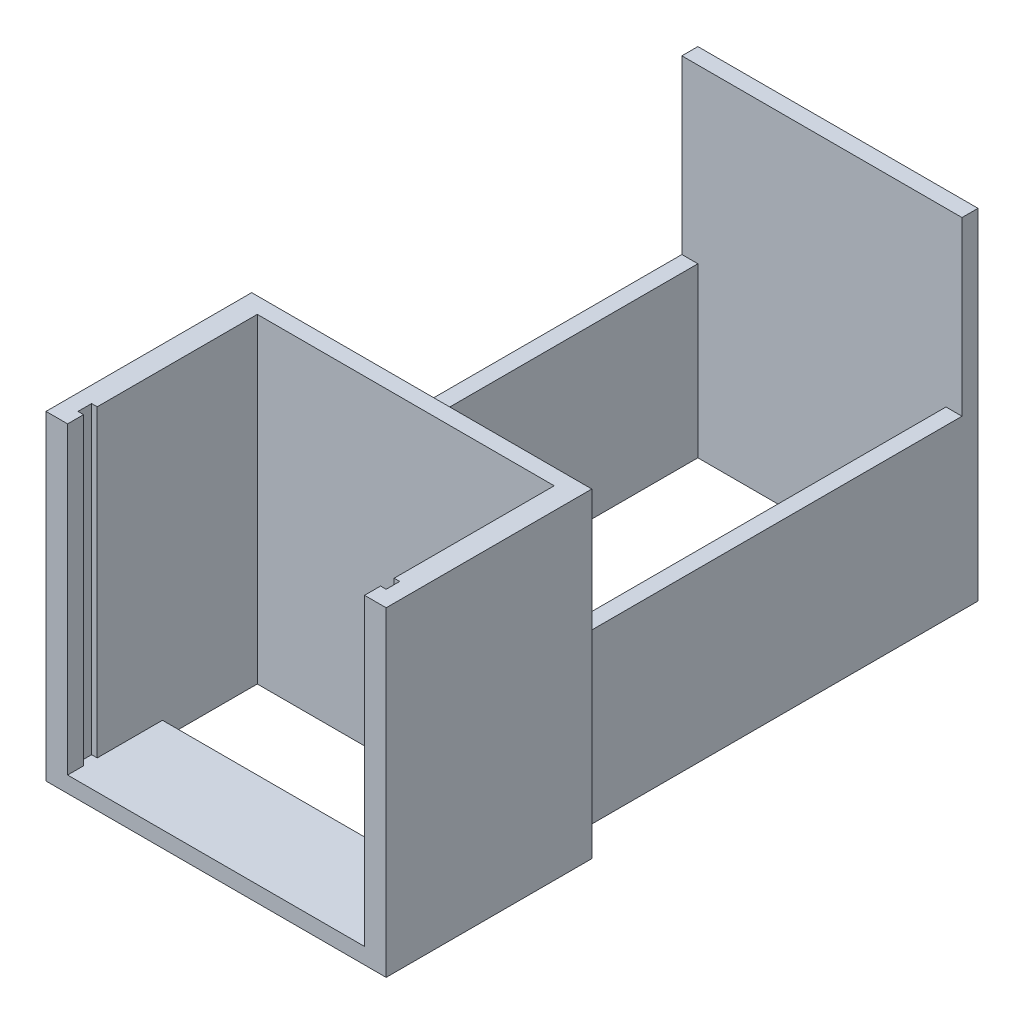
SolidWorks part; units mm, degrees
ref_plane "Front Plane" through (0, 0, 0) normal (0, 0, 1) x (1, 0, 0)
ref_plane "Top Plane" through (0, 0, 0) normal (0, 1, 0) x (1, 0, 0)
ref_plane "Right Plane" through (0, 0, 0) normal (1, 0, 0) x (0, 0, -1)
sketch "Sketch1" plane through (0, 0, 0) normal (0, 1, 0) x (1, 0, 0)
  line L5 (-62.899, -24.3935) -> (-24.399, -24.3935)
  line L6 (-62.899, -24.3935) -> (-62.899, -26.0935)
  line L7 (-62.899, -26.0935) -> (-24.399, -26.0935)
  line L8 (-24.399, -24.3935) -> (-24.399, -26.0935)
  line L9 (-62.199, -22.3935) -> (-25.099, -22.3935)
  line L10 (-62.199, -22.3935) -> (-62.199, -28.0935)
  line L11 (-62.199, -28.0935) -> (-25.099, -28.0935)
  line L12 (-25.099, -22.3935) -> (-25.099, -28.0935)
  line L13 (-64.899, -22.3935) -> (-22.399, -22.3935)
  line L14 (-64.899, -22.3935) -> (-64.899, -28.0935)
  line L15 (-64.899, -28.0935) -> (-22.399, -28.0935)
  line L16 (-22.399, -22.3935) -> (-22.399, -28.0935)
  point P8 (-24.399, -25.2435)
  dimension "D1" = 38.5
  dimension "D2" = 1.7
  dimension "D3" = 2
  dimension "D4" = 2
  dimension "D5" = 0.7
  dimension "D6" = 0.7
  dimension "D7" = 2
  dimension "D8" = 2
  dimension "D9" = 2
  dimension "D10" = 2
extrude "Boss-Extrude1" add sketch "Sketch1" along normal blind 38 contours L14 L15 L10 L7 L6 L5 L13 | L16 L13 L12 L5 L8 L7 L15
sketch "Sketch2" plane through (0, 0, 0) normal (0, 1, 0) x (1, 0, 0)
  line L1 (-64.899, -28.0935) -> (-22.399, -28.0935)
  line L2 (-64.899, -28.0935) -> (-64.899, -22.3935)
  line L3 (-64.899, -22.3935) -> (-22.399, -22.3935)
  line L4 (-22.399, -28.0935) -> (-22.399, -22.3935)
  dimension "D1" = 42.5
  dimension "D2" = 5.7
extrude "Boss-Extrude2" add sketch "Sketch2" against normal blind 2
sketch "Sketch3" plane through (0, 0, 22.3935) normal (0, 0, -1) x (-1, 0, 0)
  line L1 (22.399, 38) -> (64.899, 38)
  line L2 (22.399, 38) -> (22.399, -2)
  line L3 (22.399, -2) -> (64.899, -2)
  line L4 (64.899, 38) -> (64.899, -2)
  line L5 (25.099, 0) -> (62.199, 0)
  line L6 (25.099, 0) -> (25.099, 38)
  line L7 (25.099, 38) -> (62.199, 38)
  line L8 (62.199, 0) -> (62.199, 38)
  line M6 (62.199, 38) -> (62.199, 0)
  line M7 (62.199, 0) -> (25.099, 0)
  line M8 (25.099, 0) -> (25.099, 38)
  line M9 (25.099, 38) -> (22.399, 38)
  line M10 (22.399, 38) -> (22.399, -2)
  line M11 (22.399, -2) -> (64.899, -2)
  line M12 (64.899, -2) -> (64.899, 38)
  line M13 (64.899, 38) -> (62.199, 38)
  dimension "D1" = 42.5
  dimension "D2" = 40
  dimension "D3" = 38
  dimension "D4" = 37.1
extrude "Boss-Extrude3" add sketch "Sketch3" along normal blind 18 contours M13 M6 M7 M8 M9 M10 M11 M12
sketch "Sketch4" plane through (0, 0, 4.3935) normal (0, 0, -1) x (-1, 0, 0)
  line L1 (22.399, 38) -> (64.899, 38)
  line L2 (22.399, 38) -> (22.399, -2)
  line L3 (22.399, -2) -> (64.899, -2)
  line L4 (64.899, 38) -> (64.899, -2)
extrude "Boss-Extrude4" add sketch "Sketch4" along normal blind 2
sketch "Sketch5" plane through (0, 0, 0) normal (0, 1, 0) x (1, 0, 0)
  line L0 (-62.199, -16.2435) -> (-25.099, -16.2435)
  line L1 (-62.199, -4.3935) -> (-25.099, -4.3935)
  line L2 (-62.199, -4.3935) -> (-62.199, -28.0935)
  line L3 (-62.199, -28.0935) -> (-25.099, -28.0935)
  line L4 (-25.099, -4.3935) -> (-25.099, -28.0935)
  line M5 (-25.099, -24.3935) -> (-25.099, -4.3935)
  line M6 (-25.099, -4.3935) -> (-62.199, -4.3935)
  line M7 (-62.199, -4.3935) -> (-62.199, -24.3935)
  dimension "D1" = 37.1
  dimension "D2" = 23.7
  dimension "D3" = 11.85
extrude "Cut-Extrude1" cut sketch "Sketch5" against normal through all contours L0 M7 M5 M6
sketch "Sketch6" plane through (0, 0, 2.3935) normal (0, 0, -1) x (-1, 0, 0)
  line L1 (64.899, 38) -> (22.399, 38)
  line L2 (64.899, 38) -> (64.899, -2)
  line L3 (64.899, -2) -> (22.399, -2)
  line L4 (22.399, 38) -> (22.399, -2)
  line L17 (26.149, 19) -> (28.149, 19)
  line L18 (26.149, 19) -> (26.149, -2)
  line L19 (26.149, -2) -> (28.149, -2)
  line L20 (28.149, 19) -> (28.149, -2)
  line L21 (59.149, 19) -> (61.149, 19)
  line L22 (59.149, 19) -> (59.149, -2)
  line L23 (59.149, -2) -> (61.149, -2)
  line L24 (61.149, 19) -> (61.149, -2)
  dimension "D3" = 2
  dimension "D4" = 2
  dimension "D1" = 19
  dimension "D2" = 19
  dimension "D5" = 31
  dimension "D6" = 3.75
  dimension "D7" = 42.5
extrude "Boss-Extrude6" add sketch "Sketch6" along normal blind 50 contours L20 L17 L18 L3 | L24 L21 L22 L3
sketch "Sketch7" plane through (0, -2, 0) normal (0, -1, 0) x (1, 0, 0)
  line L1 (-61.149, -47.6065) -> (-26.149, -47.6065)
  line L2 (-61.149, -47.6065) -> (-61.149, -49.6065)
  line L3 (-61.149, -49.6065) -> (-26.149, -49.6065)
  line L4 (-26.149, -47.6065) -> (-26.149, -49.6065)
  line L6 (-61.149, -47.6065) -> (-26.149, -47.6065)
  line M11 (-61.149, -47.6065) -> (-59.149, -47.6065)
  line M15 (-28.149, -47.6065) -> (-26.149, -47.6065)
  dimension "D1" = 2
  dimension "D2" = 35
  dimension "D3" = 35
extrude "Boss-Extrude7" add sketch "Sketch7" against normal blind 42.5 contours L4 L1 L2 L3 M15 M11
equation "\"camera side length\"= 38"
equation "\"camera module panel thickness\"= 1.7"
equation "\"tolerance\"= 0.5"
equation "\"D1@Sketch1\"=\"camera side length\"+\"tolerance\""
equation "\"D2@Sketch1\"=\"camera module panel thickness\""
equation "\"camera module side clearance\"= 0.7"
equation "\"camera mount thickness\"= 2"
equation "\"D3@Sketch1\"=\"camera mount thickness\""
equation "\"D4@Sketch1\"=\"camera mount thickness\""
equation "\"D5@Sketch1\"=\"camera module side clearance\""
equation "\"D6@Sketch1\"=\"camera module side clearance\""
equation "\"D7@Sketch1\"=\"camera mount thickness\""
equation "\"D8@Sketch1\"=\"camera mount thickness\""
equation "\"D9@Sketch1\"=\"camera mount thickness\""
equation "\"D10@Sketch1\"=\"camera mount thickness\""
equation "\"D1@Boss-Extrude1\"=\"camera side length\""
equation "\"D1@Boss-Extrude2\"=\"camera mount thickness\""
equation "\"camera module hole offset\"= 4.65"
equation "\"camera module hole diameter\"= 2.33"
equation "\"camera mount inner depth\"= 20"
equation "\"D1@Boss-Extrude3\"=\"camera mount inner depth\"-\"camera mount thickness\""
equation "\"D1@Boss-Extrude4\"=\"camera mount thickness\""
equation "\"light thickness\" =20"
equation "\"D1@Sketch6\"=\"camera side length\"/2"
equation "\"D2@Sketch6\"=\"D1@Sketch6\""
equation "\"D3@Sketch6\"=\"camera mount thickness\""
equation "\"D4@Sketch6\"= \"camera mount thickness\""
equation "\"D5@Sketch6\"=31"
equation "\"D6@Sketch6\"=(\"D7@Sketch6\"-(\"D5@Sketch6\"+2*\"D3@Sketch6\"))/2"
equation "\"D1@Boss-Extrude6\"=\"light thickness\"+30"
equation "\"D1@Sketch7\"=\"camera mount thickness\""
equation "\"D2@Sketch7\"=\"D3@Sketch7\""
